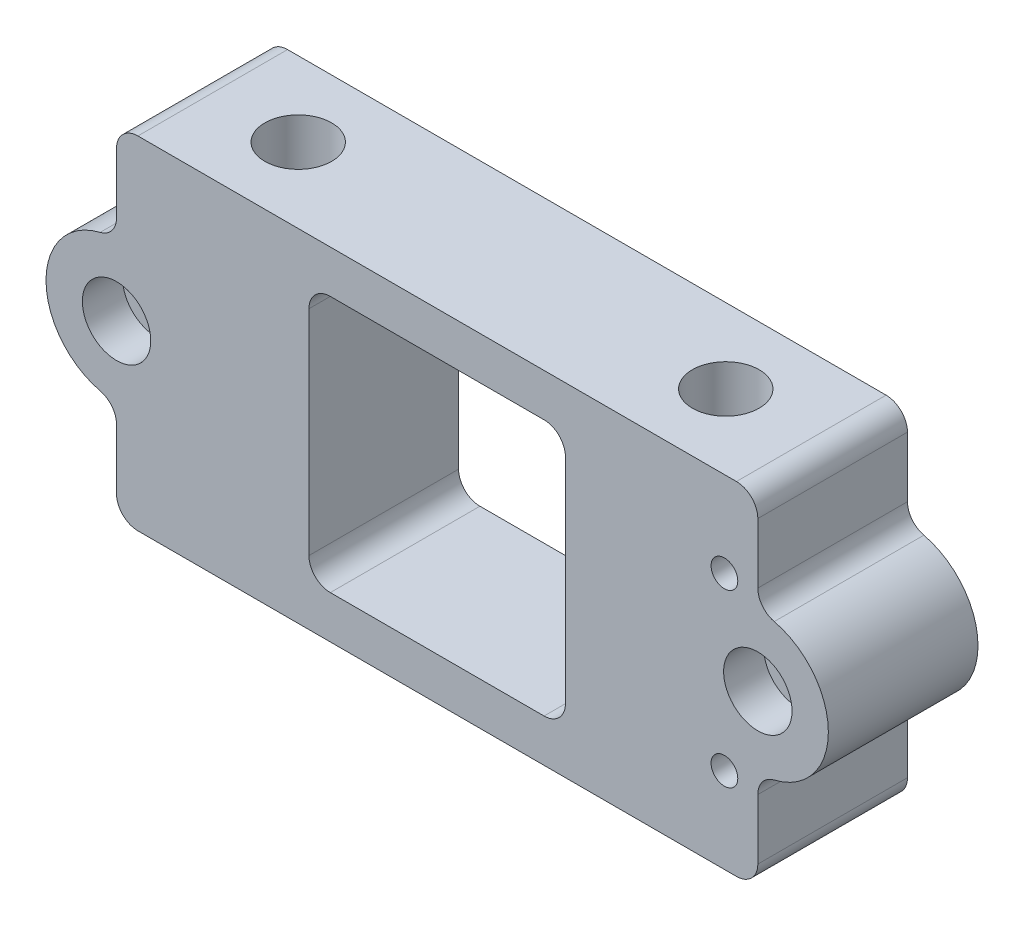
SolidWorks part; units mm, degrees
material "6061-T6 (SS)"
ref_plane "X-Y Datum" through (0, 0, 0) normal (0, 0, 1) x (1, 0, 0)
ref_plane "X-Z Datum" through (0, 0, 0) normal (0, 1, 0) x (1, 0, 0)
ref_plane "Y-Z Datum" through (0, 0, 0) normal (1, 0, 0) x (0, 0, -1)
other "Graphic1"
other "Graphic (Closed) -1"
other "Graphic2"
other "Graphic (Closed) -2"
other "Graphic3"
other "Graphic (Closed) -3"
sketch "Sketch1" plane through (0, 0, 0) normal (0, 0, 1) x (1, 0, 0)
  line L5 (-93.6625, 0) -> (0, 0) construction
  line L7 (-93.6625, -20.32) -> (-93.6625, 20.32)
  line L17 (-93.6625, -20.32) -> (0, -20.32)
  line L28 (-12.7, 15.2978) -> (-12.7, -16.3411) construction
  line L30 (-93.6625, 20.32) -> (0, 20.32)
  line L31 (0, 20.32) -> (0, -20.32)
  circle A4 centre (-84.9313, 0) radius 2.4892
  circle A7 centre (-8.7312, 0) radius 2.4892
  circle A8 centre (-12.7, 10.16) radius 1.5875
  circle A9 centre (-12.7, -10.16) radius 1.5875
  point P1 (-93.6625, 0)
  point P15 (-14.5042, 10.16)
  dimension "D2" = 93.6625
  dimension "D3" = 8.7312
  dimension "D5" = 3.175
  dimension "D1" = 8.7312
  dimension "D4" = 40.64
  dimension "D6" = 10.16
  dimension "D7" = 10.16
  dimension "D8" = 12.7
extrude "Boss-Extrude1" add sketch "Sketch1" against normal blind 17.78
sketch "Sketch3" plane through (0, 0, 0) normal (0, 0, 1) x (1, 0, 0)
  circle A2 centre (-84.9313, 0) radius 4.064
  circle A3 centre (-84.9313, 0) radius 2.4892 construction
  circle A4 centre (-8.7312, 0) radius 4.064
  dimension "D1" = 8.128
sketch "Sketch6" plane through (0, 20.32, 0) normal (0, 1, 0) x (1, 0, 0)
  line L0 (0, 17.78) -> (-93.6625, 17.78) construction
  line L1 (-72.2313, 8.89) -> (-21.4312, 8.89) construction
  circle A0 centre (-72.2313, 8.89) radius 3.9687
  circle A1 centre (-21.4312, 8.89) radius 3.9687
  point P4 (-46.8312, 17.78)
  point P5 (-46.8312, 8.89)
  dimension "D1" = 7.9375
  dimension "D2" = 8.89
  dimension "D3" = 50.8
extrude "Cut-Extrude4" cut sketch "Sketch6" against normal through all
sketch "Sketch5" plane through (0, 0, 0) normal (0, 0, 1) x (1, 0, 0)
  line L7 (-46.8312, 20.32) -> (-46.8313, -20.32) construction
  line L8 (0, 20.32) -> (-93.6625, 20.32) construction
  line L18 (-93.6625, -20.32) -> (0, -20.32) construction
  line B0 (-93.6625, -20.32) -> (-93.6625, 20.32)
  line B1 (-84.9312, -20.32) -> (-93.6625, -20.32)
  line B2 (-84.9313, -10.6225) -> (-84.9312, -20.32)
  line B3 (-84.9313, 10.6225) -> (-84.9312, 20.32)
  line B4 (-93.6625, 20.32) -> (-84.9312, 20.32)
  arc B5 (-84.9313, -10.6225) -> (-86.8806, -8.1522) centre (-87.4713, -10.6225) ccw
  arc B6 (-86.8806, 8.1522) -> (-86.8806, -8.1522) centre (-84.9313, 0) ccw
  arc B7 (-84.9313, 10.6225) -> (-86.8806, 8.1522) centre (-87.4713, 10.6225) cw
  line B8 (0, -20.32) -> (0, 20.32)
  line B9 (-8.7313, -20.32) -> (0, -20.32)
  line B10 (-8.7313, -10.6225) -> (-8.7313, -20.32)
  line B11 (-8.7312, 10.6225) -> (-8.7312, 20.32)
  line B12 (0, 20.32) -> (-8.7312, 20.32)
  arc B13 (-8.7313, -10.6225) -> (-6.7819, -8.1522) centre (-6.1912, -10.6225) cw
  arc B14 (-6.7819, 8.1522) -> (-6.7819, -8.1522) centre (-8.7312, 0) cw
  arc B15 (-8.7312, 10.6225) -> (-6.7819, 8.1522) centre (-6.1912, 10.6225) ccw
sketch_block_instance "Block1-1"
sketch_block "Block1"
sketch_block_instance "Block1-2"
extrude "Cut-Extrude3" cut sketch "Sketch5" against normal up to surface (17.78 mm away) up to face at (-11.1125, -10.16, -17.78)
fillet "Fillet1" radius 2.54 4 edges at (-84.9312, -20.32, -8.89) (-8.7313, -20.32, -8.89) (-8.7312, 20.32, -8.89) (-84.9312, 20.32, -8.89)
extrude "Cut-Extrude5" cut sketch "Sketch3" against normal blind 4.7752
ref_point "Point1"
ref_point "Point2"
sketch "Sketch7" plane through (0, 0, 0) normal (0, 0, 1) x (1, 0, 0)
  line L0 (-46.8312, 20.32) -> (-46.8313, -20.32) construction
  line L5 (-11.2713, 20.32) -> (-82.3912, 20.32) construction
  line L6 (-82.3912, -20.32) -> (-11.2713, -20.32) construction
  line L8 (-59.5313, -15.24) -> (-34.1313, -15.24)
  line L9 (-62.0713, -12.7) -> (-62.0713, 12.7)
  line L10 (-59.5313, 15.24) -> (-34.1313, 15.24)
  line L11 (-31.5913, -12.7) -> (-31.5913, 12.7)
  line L12 (-62.0712, -15.24) -> (-31.5913, 15.24) construction
  line L13 (-62.0712, 15.24) -> (-31.5913, -15.24) construction
  arc A0 (-59.5313, -15.24) -> (-62.0713, -12.7) centre (-59.5313, -12.7) cw
  arc A1 (-34.1313, -15.24) -> (-31.5913, -12.7) centre (-34.1313, -12.7) ccw
  arc A2 (-34.1313, 15.24) -> (-31.5913, 12.7) centre (-34.1313, 12.7) cw
  arc A3 (-62.0713, 12.7) -> (-59.5313, 15.24) centre (-59.5313, 12.7) cw
  point P0 (-46.8313, 0)
  dimension "D3" = 2.54
  dimension "D1" = 30.48
  dimension "D2" = 30.48
extrude "Cut-Extrude6" cut sketch "Sketch7" against normal through all
